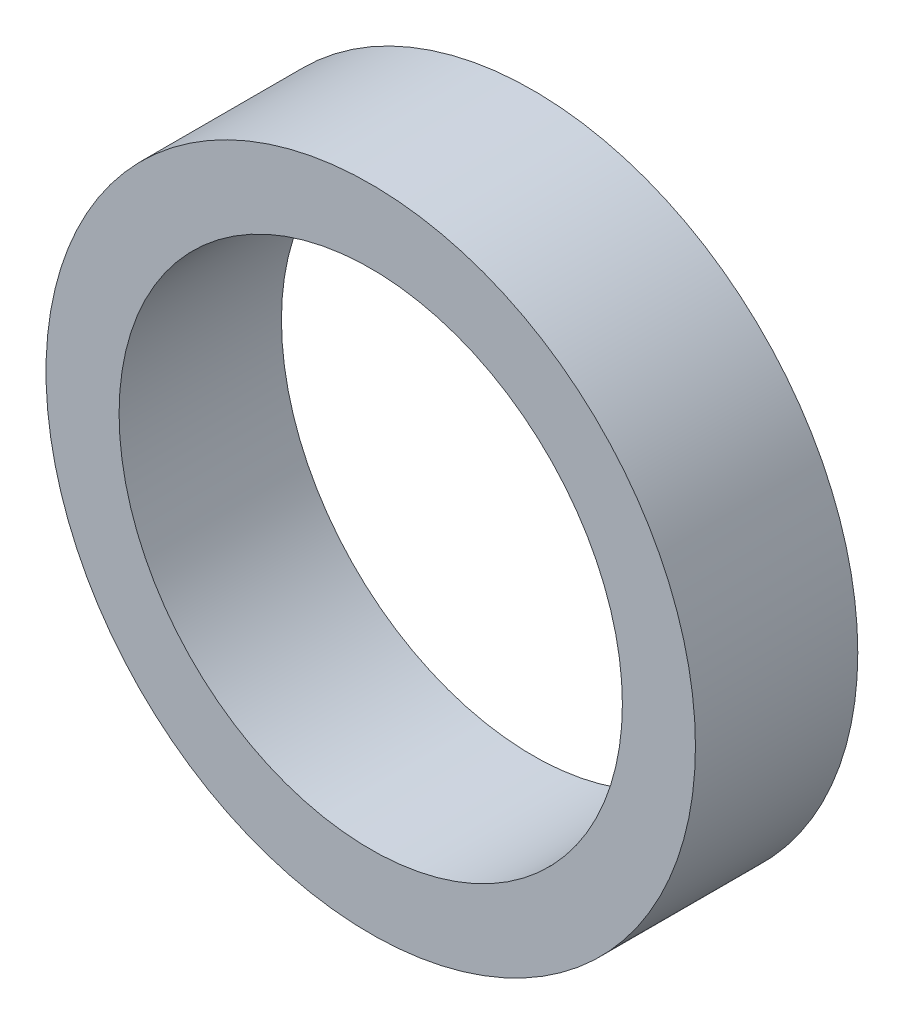
SolidWorks part; units mm, degrees
ref_plane "Front Plane" through (0, 0, 0) normal (0, 0, 1) x (1, 0, 0)
ref_plane "Top Plane" through (0, 0, 0) normal (0, 1, 0) x (1, 0, 0)
ref_plane "Right Plane" through (0, 0, 0) normal (1, 0, 0) x (0, 0, -1)
sketch "Sketch1" plane through (0, 0, 0) normal (0, 0, 1) x (1, 0, 0)
  circle A0 centre (0, 0) radius 2
  circle A1 centre (0, 0) radius 1.55
  dimension "D1" = 4
  dimension "D2" = 3.1
extrude "Boss-Extrude1" add sketch "Sketch1" along normal blind 1
